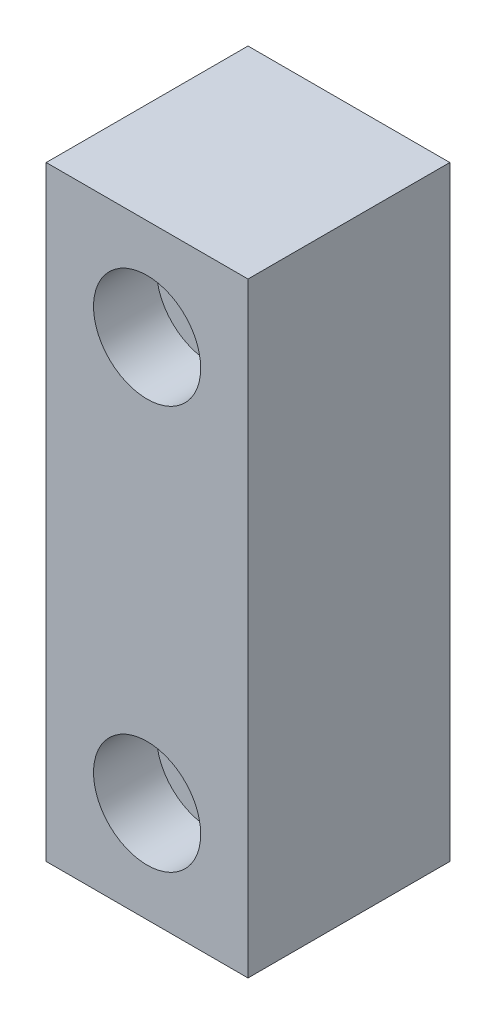
SolidWorks part; units mm, degrees
ref_plane "Front Plane" through (0, 0, 0) normal (1, 0, 0) x (0, 1, 0)
ref_plane "Top Plane" through (0, 0, 0) normal (0, 0, 1) x (0, 1, 0)
ref_plane "Right Plane" through (0, 0, 0) normal (0, 1, 0) x (-1, 0, 0)
sketch "Sketch1" plane through (0, 0, 0) normal (0, 0, 1) x (0, 1, 0)
  line L1 (-38.1, -12.7) -> (38.1, -12.7)
  line L2 (-38.1, -12.7) -> (-38.1, 12.7)
  line L3 (-38.1, 12.7) -> (38.1, 12.7)
  line L4 (38.1, -12.7) -> (38.1, 12.7)
  line L5 (-38.1, -12.7) -> (38.1, 12.7) construction
  line L6 (-38.1, 12.7) -> (38.1, -12.7) construction
  point P0 (0, 0)
extrude "Boss-Extrude1" add sketch "Sketch1" along normal mid plane 25.4
hole_wizard "CBORE for 5/16 Socket Head Cap Screw1" positions "Sketch3" profile "Sketch2" counterbore size "5/16" standard "ANSI Inch"
sketch "Sketch3" plane through (0, 0, 12.7) normal (0, 0, 1) x (1, 0, 0)
  line L0 (0, -25.4) -> (0, 25.4) construction
  point P0 (0, -25.4)
  point P1 (0, 25.4)
sketch "Sketch2" plane through (0, -25.4, 12.7) normal (1, 0, 0) x (0, -1, 0)
  line L0 (0, 0) -> (0, 28.025)
  line L1 (0, 28.025) -> (4.3688, 25.4)
  line L2 (4.3688, 25.4) -> (4.3688, 7.9248)
  line L3 (4.3688, 7.9248) -> (6.7437, 7.9248)
  line L4 (6.7437, 7.9248) -> (6.7437, 0)
  line L5 (6.7437, 0) -> (0, 0)
  line L10 (0, 28.025) -> (-4.3688, 25.4) construction
  line L11 (0, -6.35) -> (0, 107.95) construction
  dimension "Hole Dia." = 8.7376
  dimension "Hole Depth" = 25.4
  dimension "C'Bore Dia." = 13.4874
  dimension "C'Bore Depth" = 7.9248
  dimension "Drill Angle" = 118
